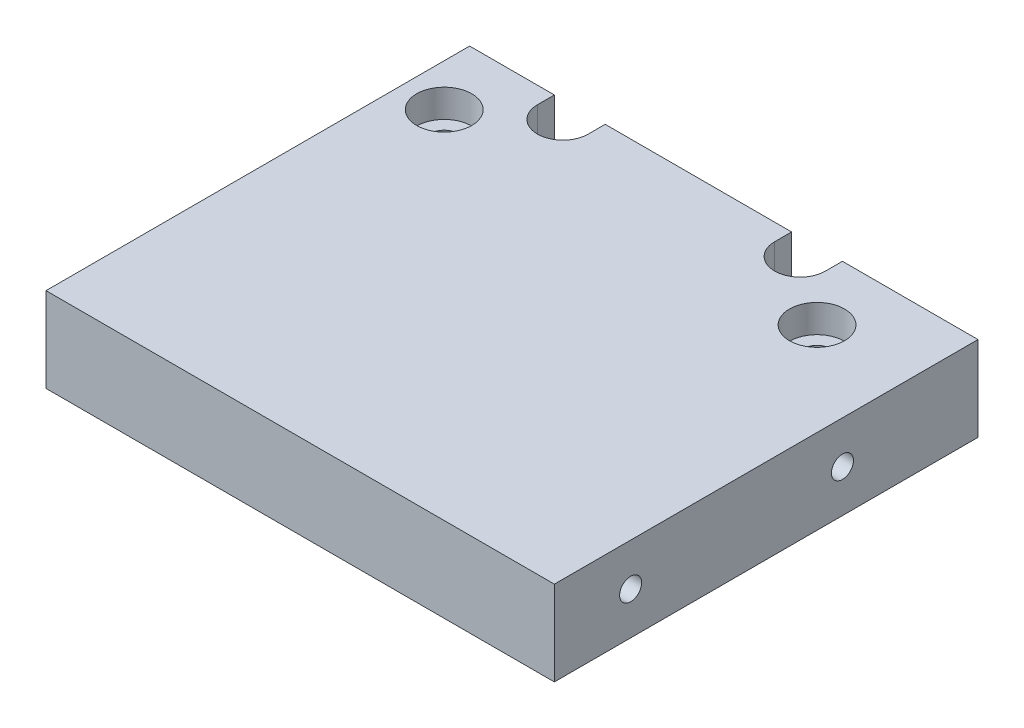
SolidWorks part; units mm, degrees
ref_plane "Front Plane" through (0, 0, 0) normal (0, 0, 1) x (1, 0, 0)
ref_plane "Top Plane" through (0, 0, 0) normal (0, 1, 0) x (1, 0, 0)
ref_plane "Right Plane" through (0, 0, 0) normal (1, 0, 0) x (0, 0, -1)
sketch "Sketch1" plane through (0, 0, 0) normal (0, 1, 0) x (1, 0, 0)
  line L1 (0, 0) -> (60, 0)
  line L2 (0, 0) -> (0, 50)
  line L3 (0, 50) -> (60, 50)
  line L4 (60, 0) -> (60, 50)
  line L5 (0, 0) -> (60, 50) construction
  line L6 (0, 50) -> (60, 0) construction
  point P4 (30, 25)
extrude "Boss-Extrude1" add sketch "Sketch1" along normal blind 10 contours L3 L4 L1 L2
sketch "Sketch2" plane through (0, 10, 0) normal (0, 1, 0) x (1, 0, 0)
  line L0 (38, 48) -> (38, 50)
  line L2 (10, 48) -> (10, 50)
  line L3 (10, 50) -> (16, 50)
  line L4 (16, 48) -> (16, 50)
  line L5 (10, 48) -> (16, 50) construction
  line L6 (10, 50) -> (16, 48) construction
  line L7 (38, 50) -> (44, 50)
  line L8 (44, 48) -> (44, 50)
  line L9 (38, 48) -> (44, 50) construction
  line L10 (38, 50) -> (44, 48) construction
  arc A1 (10, 48) -> (16, 48) centre (13, 48) ccw
  arc A2 (38, 48) -> (44, 48) centre (41, 48) ccw
  point P4 (13, 49)
  point P10 (41, 49)
extrude "Cut-Extrude1" cut sketch "Sketch2" against normal blind 10
sketch "Sketch3" plane through (0, 0, 0) normal (1, 0, 0) x (0, 0, -1)
  line L0 (45, 0) -> (50, 0)
  line L3 (45, 0) -> (45, 10)
  line L4 (45, 10) -> (50, 5)
  line L5 (50, 5) -> (50, 0)
extrude "Boss-Extrude2" add sketch "Sketch3" along normal through all
hole_wizard "CBORE for M3 Pan Head Screw1" positions "3DSketch1" profile "Sketch4" counterbore size "M3" standard "JIS" end condition through all
sketch3d "3DSketch1"
  point P0 (5, 10, -42)
  point P2 (49, 10, -42)
sketch "Sketch4" plane through (5, 10, -42) normal (1, 0, 0) x (0, 0, 1)
  line L0 (0, 0) -> (0, 10)
  line L1 (0, 10) -> (1.7, 10)
  line L3 (1.7, 10) -> (1.7, 3.3)
  line L4 (1.7, 3.3) -> (3.25, 3.3)
  line L5 (3.25, 3.3) -> (3.25, 0)
  line L7 (3.25, 0) -> (0, 0)
  line L11 (0, -6.35) -> (0, 107.95) construction
  dimension "Thru Hole Dia." = 3.4
  dimension "Thru Hole Depth" = 10
  dimension "C'Bore Dia." = 6.5
  dimension "C'Bore Depth" = 3.3
sketch "Sketch5" plane through (60, 0, 0) normal (1, 0, 0) x (0, 0, -1)
  point P0 (34, 5)
  point P2 (9, 5)
hole_wizard "M3x0.5 Tapped Hole1" positions "Sketch5" profile "Sketch6" tap size "M3x0.5" standard "JIS"
sketch "Sketch6" plane through (60, 5, -34) normal (0, 1, 0) x (0, 0, -1)
  line L0 (0, 0) -> (0, 9.7811)
  line L1 (0, 9.7811) -> (1.3, 9)
  line L2 (1.3, 9) -> (1.3, 0)
  line L5 (1.3, 0) -> (0, 0)
  line L10 (0, 9.7811) -> (-1.3, 9) construction
  line L11 (0, -6.35) -> (0, 107.95) construction
  dimension "Tap Drill Dia." = 2.6
  dimension "Tap Drill Depth" = 9
  dimension "Drill Angle" = 118
cosmetic thread "Hole Thread1" parameters "D1"=6, "D2"=3
cosmetic thread "Hole Thread2" parameters "D1"=6, "D2"=3
sketch "Sketch7" plane through (0, 0, 0) normal (-1, 0, 0) x (0, 0, 1)
  point P0 (-34, 5)
  point P2 (-9, 5)
hole_wizard "M3x0.5 Tapped Hole2" positions "Sketch7" profile "Sketch8" tap size "M3x0.5" standard "JIS"
sketch "Sketch8" plane through (0, 5, -34) normal (0, 1, 0) x (0, 0, 1)
  line L0 (0, 0) -> (0, 9.7811)
  line L1 (0, 9.7811) -> (1.3, 9)
  line L2 (1.3, 9) -> (1.3, 0)
  line L5 (1.3, 0) -> (0, 0)
  line L10 (0, 9.7811) -> (-1.3, 9) construction
  line L11 (0, -6.35) -> (0, 107.95) construction
  dimension "Tap Drill Dia." = 2.6
  dimension "Tap Drill Depth" = 9
  dimension "Drill Angle" = 118
cosmetic thread "Hole Thread3" parameters "D1"=6, "D2"=3
cosmetic thread "Hole Thread4" parameters "D1"=6, "D2"=3
